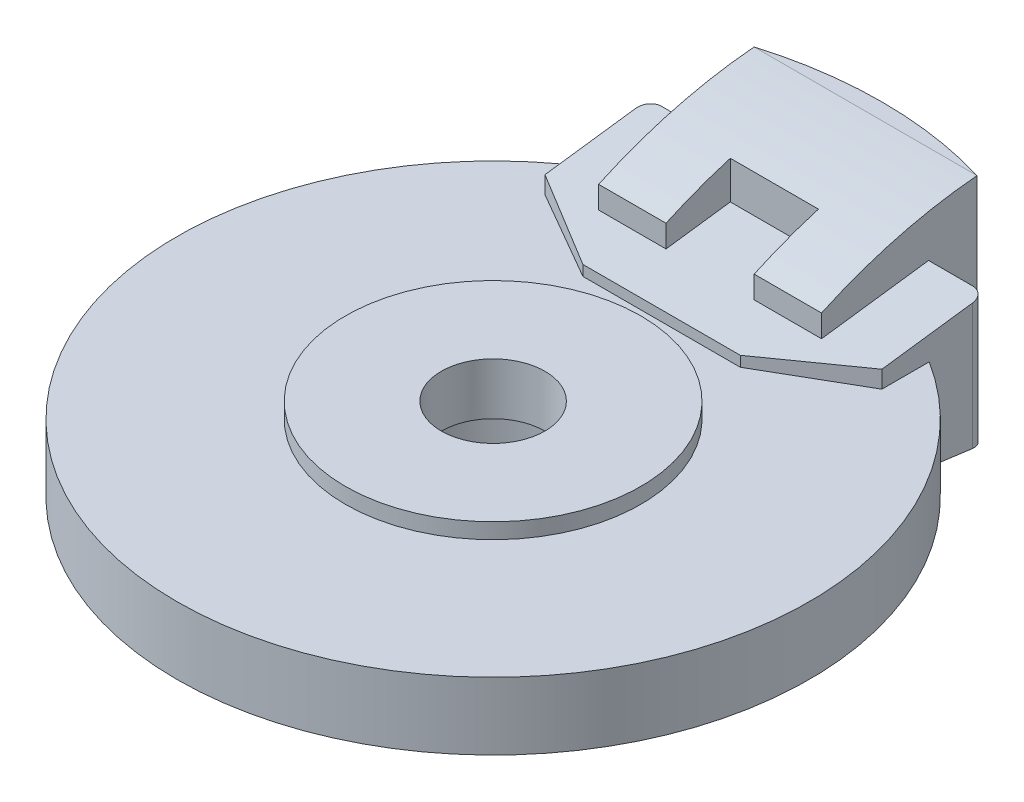
SolidWorks part; units mm, degrees
ref_plane "Front Plane" through (0, 0, 0) normal (0, 0, 1) x (1, 0, 0)
ref_plane "Top Plane" through (0, 0, 0) normal (0, 1, 0) x (1, 0, 0)
ref_plane "Right Plane" through (0, 0, 0) normal (1, 0, 0) x (0, 0, -1)
sketch "Sketch1" plane through (0, 0, 0) normal (0, 1, 0) x (1, 0, 0)
  circle A0 centre (0, 0) radius 6.1
  dimension "D1" = 12.2
extrude "Boss-Extrude1" add sketch "Sketch1" along normal blind 1.3
sketch "Sketch2" plane through (0, 1.3, 0) normal (0, 1, 0) x (1, 0, 0)
  circle A0 centre (0, 0) radius 2.85
  dimension "D1" = 5.7
extrude "Boss-Extrude2" add sketch "Sketch2" along normal blind 0.3
sketch "Sketch5" plane through (0, 0, 0) normal (0, -1, 0) x (1, 0, 0)
  circle A0 centre (0, 0) radius 3.45
  dimension "D1" = 6.9
extrude "Boss-Extrude3" add sketch "Sketch5" along normal blind 0.2
hole_wizard "Ø2.0mm Dowel Hole1" positions "Sketch3" profile "Sketch4" hole size "Ø2.0" standard "ANSI Metric"
sketch "Sketch3" plane through (0, 1.6, 0) normal (0, 1, 0) x (1, 0, 0)
  point P0 (0, 0)
sketch "Sketch4" plane through (0, 1.6, 0) normal (1, 0, 0) x (0, 0, 1)
  line L0 (0, 0) -> (0, 52.9209)
  line L1 (0, 52.9209) -> (1, 52.32)
  line L2 (1, 52.32) -> (1, 0)
  line L5 (1, 0) -> (0, 0)
  line L10 (0, 52.9209) -> (-1, 52.32) construction
  line L11 (0, -6.35) -> (0, 107.95) construction
  dimension "Hole Dia." = 2
  dimension "Hole Depth" = 52.32
  dimension "Drill Angle" = 118
sketch "Sketch6" plane through (0, -0.2, 0) normal (0, -1, 0) x (1, 0, 0)
  circle A0 centre (0, 0) radius 2.6
  circle A1 centre (0, 0) radius 2.1
  dimension "D1" = 5.2
  dimension "D2" = 0.5
extrude "Boss-Extrude4" add sketch "Sketch6" along normal blind 0.8
sketch "Sketch8" plane through (0, -1, 0) normal (0, -1, 0) x (1, 0, 0)
  circle A0 centre (0, 0) radius 2.1
extrude "Cut-Extrude1" cut sketch "Sketch8" against normal blind 1.6
sketch "Sketch9" plane through (0, 0, 0) normal (0, 1, 0) x (1, 0, 0)
  line L0 (-3.25, 3.25) -> (3.25, 3.25)
  line L1 (3.25, 3.25) -> (3.25, 6.25)
  line L2 (3.25, 6.25) -> (-3.25, 6.25)
  line L3 (-3.25, 6.25) -> (-3.25, 3.25)
  circle A0 centre (0, 0) radius 2.85 construction
  point P2 (0, 3.25)
  dimension "D1" = 3.25
  dimension "D2" = 3
extrude "Boss-Extrude5" add sketch "Sketch9" along normal blind 1.9 and the other way blind 0.6 contours L3 L0 L1 L2
chamfer "Chamfer1" distance 1 angle 60 4 edges at (-3.25, -0.3, -3.25) (-3.25, 1.6, -3.25) (3.25, -0.3, -3.25) (3.25, 1.6, -3.25)
sketch "Sketch10" plane through (3.25, 0, 0) normal (1, 0, 0) x (0, 0, -1)
  line L0 (3.25, 1.5002) -> (6.25, 1.9)
  line L1 (3.25, 1.3) -> (3.25, 1.9) construction
  line L2 (6.25, 1.9) -> (3.25, 1.9)
  line L3 (3.25, 1.9) -> (3.25, 1.5002)
  line L4 (3.25, -0.6) -> (6.25, -0.6)
  line L5 (6.25, -0.6) -> (3.25, -0.2)
  line L6 (3.25, -0.2) -> (3.25, -0.6)
  dimension "D1" = 7.59
extrude "Cut-Extrude2" cut sketch "Sketch10" against normal through all and the other way through all
sketch "Sketch11" plane through (0, 0, 0) normal (0, 1, 0) x (1, 0, 0)
  line L0 (-2.15, 7.1852) -> (-2.15, 4.1852)
  line L1 (-2.15, 4.1852) -> (-0.85, 4.1852)
  line L2 (-0.85, 4.1852) -> (-0.85, 5.4255)
  line L3 (-0.85, 5.4255) -> (0.85, 5.4255)
  line L4 (0.85, 5.4255) -> (0.85, 4.1852)
  line L5 (0.85, 4.1852) -> (2.15, 4.1852)
  line L6 (2.15, 4.1852) -> (2.15, 7.1852)
  arc A0 (-2.15, 7.1852) -> (2.15, 7.1852) centre (0, 0) cw
  circle A1 centre (0, 0) radius 2.1 construction
  point P11 (0, 7.5)
  dimension "D1" = 5.4
  dimension "D2" = 1.3
  dimension "D3" = 1.3
  dimension "D4" = 3
  dimension "D5" = 3
  dimension "D6" = 4.3
extrude "Boss-Extrude6" add sketch "Sketch11" along normal blind 2.2 and the other way blind 2 from offset 0.65
sketch "Sketch12" plane through (-2.15, 0, 0) normal (-1, 0, 0) x (0, 0, 1)
  line L0 (-4.1852, 1.6249) -> (-4.1852, 2.85) construction
  line L3 (-4.1852, -1.35) -> (-4.1852, -0.3247) construction
  line L4 (-7.1852, 2.85) -> (-4.1852, 2.85)
  line L5 (-4.1852, 2.85) -> (-4.1852, 2.0549)
  line L6 (-4.1852, -0.7547) -> (-4.1852, -1.35)
  line L7 (-4.1852, -1.35) -> (-7.1852, -1.35)
  arc A0 (-7.1852, 2.85) -> (-4.1852, 2.0549) centre (-7.9542, -6.1082) cw
  arc A1 (-7.1852, -1.35) -> (-4.1852, -0.7547) centre (-7.4095, 7.6372) ccw
  dimension "D3" = 8.9912
  dimension "D4" = 8.99
  dimension "D1" = 0.43
  dimension "D2" = 0.43
extrude "Cut-Extrude3" cut sketch "Sketch12" against normal blind 10
fillet "Fillet1" radius 0.25 2 edges at (3.25, 0.65, -6.25) (-3.25, 0.65, -6.25)
